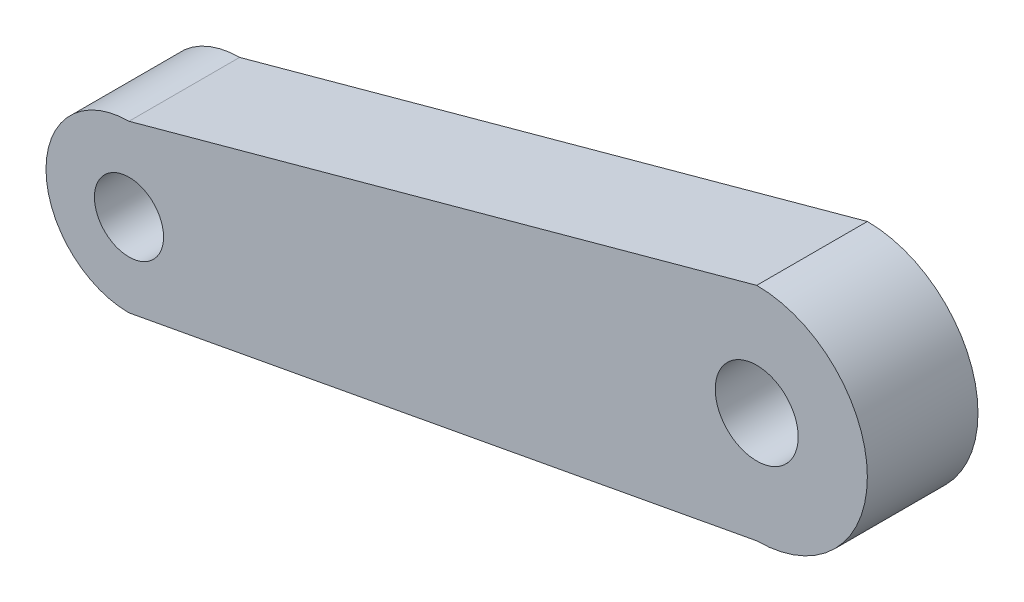
SolidWorks part; units mm, degrees
ref_plane "Спереди" through (0, 0, 0) normal (0, 0, 1) x (1, 0, 0)
ref_plane "Сверху" through (0, 0, 0) normal (0, 1, 0) x (1, 0, 0)
ref_plane "Справа" through (0, 0, 0) normal (1, 0, 0) x (0, 0, -1)
sketch "Эскиз1" plane through (0, 0, 0) normal (0, 0, 1) x (1, 0, 0)
  line L1 (-33.2939, -2.68) -> (12.0971, 9.7398)
  line L2 (-33.2939, -14.68) -> (12.0971, -6.2602)
  arc A0 (12.0971, -6.2602) -> (12.0971, 9.7398) centre (12.0971, 1.7398) ccw
  arc A1 (-33.2939, -2.68) -> (-33.2939, -14.68) centre (-33.2939, -8.68) ccw
  circle A2 centre (12.0971, 1.7398) radius 3
  circle A3 centre (-33.2939, -8.68) radius 2.5
  point P3 (0, 0)
  point P9 (0, 0)
extrude "Вытянуть1" add sketch "Эскиз1" along normal blind 8
